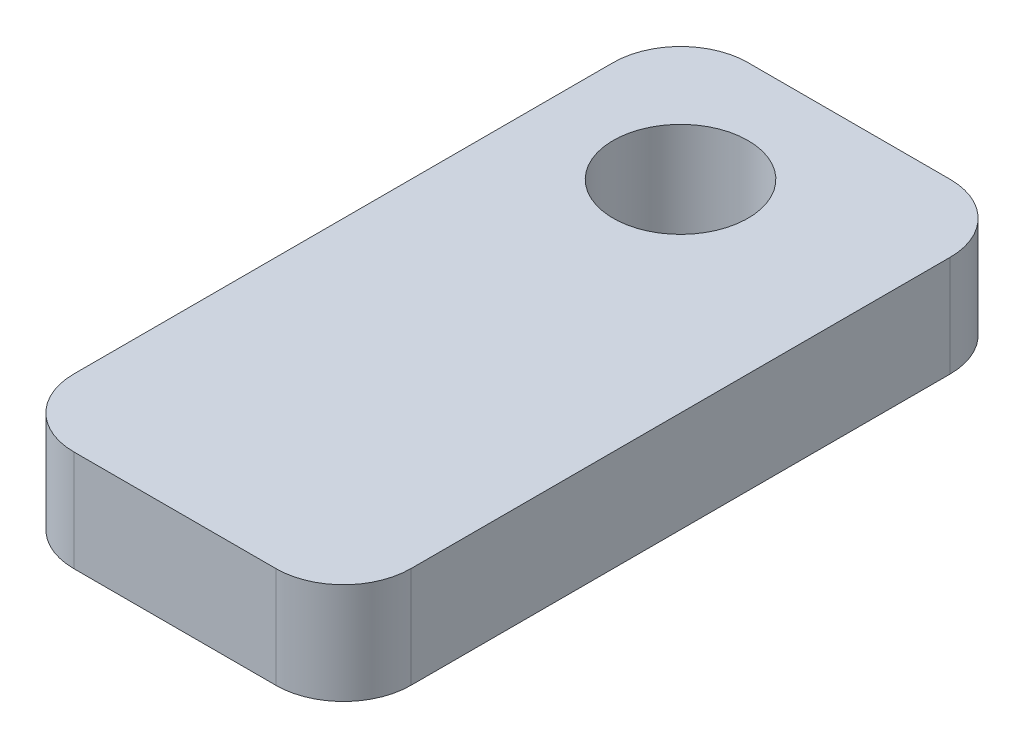
SolidWorks part; units mm, degrees
ref_plane "Plane XZ" through (0, 0, 0) normal (0, 0, 1) x (1, 0, 0)
ref_plane "Plane XY" through (0, 0, 0) normal (0, 1, 0) x (1, 0, 0)
ref_plane "Plane YZ" through (0, 0, 0) normal (1, 0, 0) x (0, 0, -1)
sketch "Sketch1" plane through (0, 0, 0) normal (0, 1, 0) x (1, 0, 0)
  line L1 (-2.54, 2.54) -> (3.81, 2.54)
  line L2 (-2.54, 2.54) -> (-2.54, -10.16)
  line L3 (-2.54, -10.16) -> (3.81, -10.16)
  line L4 (3.81, 2.54) -> (3.81, -10.16)
  circle A0 centre (0, 0) radius 1.27
  dimension "D1" = 2.54
  dimension "D2" = 2.54
  dimension "D4" = 3.81
  dimension "D5" = 10.16
  dimension "D3" = 2.54
extrude "Boss-Extrude1" add sketch "Sketch1" along normal blind 1.905
fillet "Fillet1" radius 1.27 4 edges at (-2.54, 0.9525, -2.54) (3.81, 0.9525, -2.54) (3.81, 0.9525, 10.16) (-2.54, 0.9525, 10.16)
